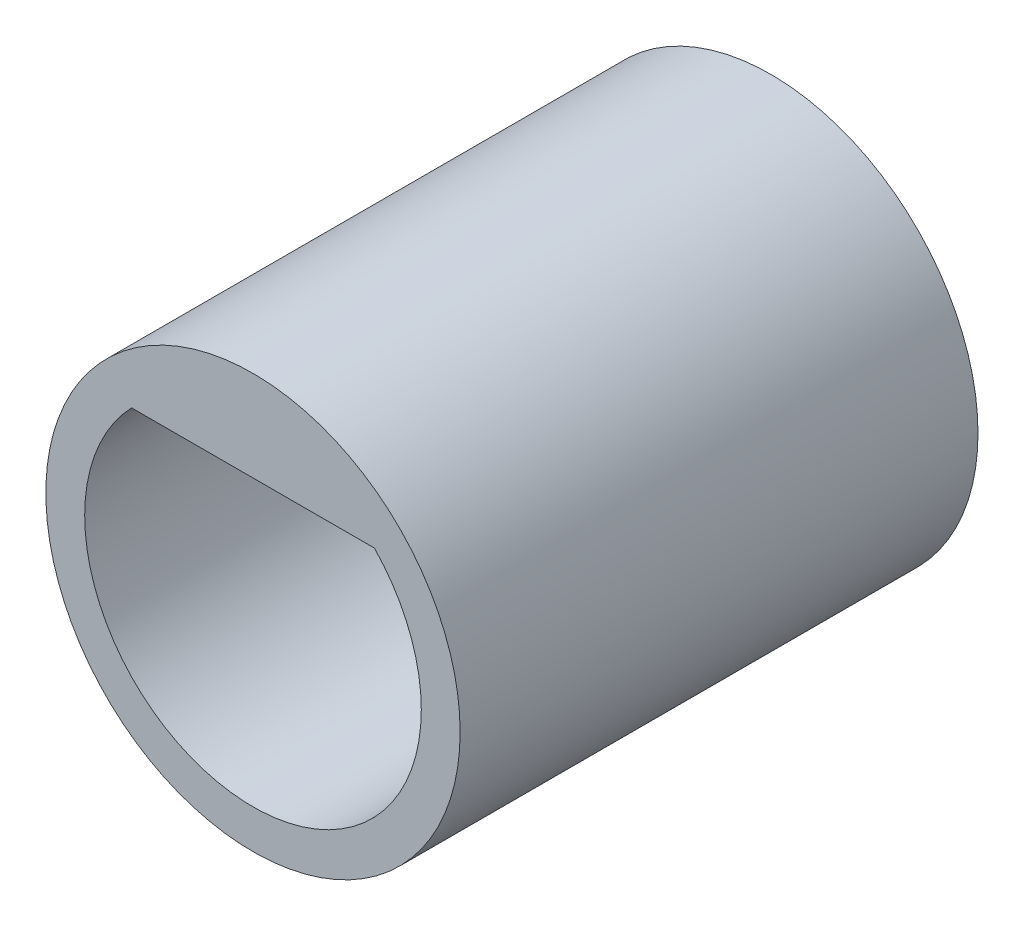
SolidWorks part; units mm, degrees
ref_plane "Front" through (0, 0, 0) normal (0, 0, 1) x (1, 0, 0)
ref_plane "Top" through (0, 0, 0) normal (0, 1, 0) x (1, 0, 0)
ref_plane "Right" through (0, 0, 0) normal (1, 0, 0) x (0, 0, -1)
sketch "Sketch1" plane through (0, 0, 0) normal (0, 0, 1) x (1, 0, 0)
  line L0 (-1.1726, 1.125) -> (1.1726, 1.125)
  circle A0 centre (0, 0) radius 2
  circle A1 centre (0, 0) radius 1.625
  point P6 (0, -1.625)
  dimension "D2" = 3.25
  dimension "D1" = 4
  dimension "D3" = 2.75
extrude "Boss-Extrude1" add sketch "Sketch1" along normal blind 5 contours L0 A1 | A0 A1
equation "\"D3@Sketch1\"=\"axle_cut\"+\"axle_room\""
equation "\"axle_dia\"= 3"
equation "\"axle_cut\"= 2.5"
equation "\"axle_room\"= 0.25"
equation "\"D1@Sketch1\"=\"magnet_hole_dia\""
equation "\"D2@Sketch1\"=\"axle_dia\"+\"axle_room\""
equation "\"magnet_hole_dia\"= 4"
